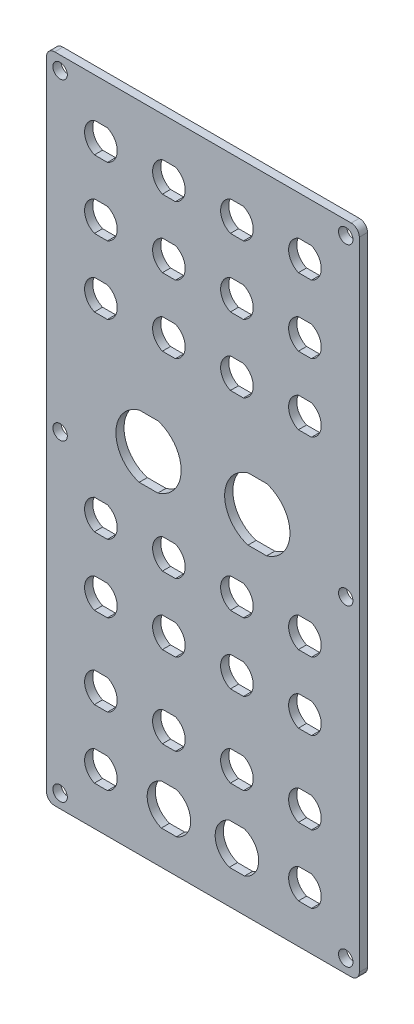
SolidWorks part; units mm, degrees
ref_plane "Front Plane" through (0, 0, 0) normal (0, 0, 1) x (1, 0, 0)
ref_plane "Top Plane" through (0, 0, 0) normal (0, 1, 0) x (1, 0, 0)
ref_plane "Right Plane" through (0, 0, 0) normal (1, 0, 0) x (0, 0, -1)
sketch "Sketch1" plane through (0, 0, 0) normal (0, 0, 1) x (1, 0, 0)
  line L1 (0, 0) -> (115, 0)
  line L2 (0, 0) -> (0, 240)
  line L3 (0, 240) -> (115, 240)
  line L4 (115, 0) -> (115, 240)
  dimension "D1" = 240
  dimension "D2" = 115
extrude "Boss-Extrude1" add sketch "Sketch1" along normal blind 3
sketch "Sketch2" plane through (0, 0, 3) normal (0, 0, 1) x (1, 0, 0)
  line L0 (20, 14.5) -> (20, 25.5) construction
  line L1 (22.3979, 25.5) -> (17.6021, 25.5)
  line L2 (22.3979, 14.5) -> (17.6021, 14.5)
  line L3 (0, 0) -> (115, 0) construction
  line L4 (0, 240) -> (0, 0) construction
  arc A0 (17.6021, 25.5) -> (17.6021, 14.5) centre (20, 20) ccw
  arc A1 (22.3979, 14.5) -> (22.3979, 25.5) centre (20, 20) ccw
  point P7 (20, 20)
  dimension "D2" = 12
  dimension "D1" = 11
  dimension "D3" = 20
  dimension "D4" = 20
extrude "Cut-Extrude1" cut sketch "Sketch2" against normal up to surface (3 mm away) up to face at (57.5, 120, 0)
pattern_linear "LPattern1" count 4 spacing 25 along (1, 0, 0) count 2 spacing 25 along (0, 1, 0) skipping (1, 0), (2, 0) of "Cut-Extrude1"
sketch "Sketch3" plane through (0, 0, 3) normal (0, 0, 1) x (1, 0, 0)
  line L0 (0, 120) -> (115, 120) construction
  line L1 (0, 240) -> (0, 0) construction
  line L2 (115, 0) -> (115, 240) construction
  line L3 (17.6021, 14.5) -> (22.3979, 14.5) construction
  line L4 (22.3979, 25.5) -> (17.6021, 25.5) construction
  line L5 (17.6021, 14.5) -> (22.3979, 14.5) construction
  line L6 (22.3979, 25.5) -> (17.6021, 25.5) construction
  line L7 (22.3979, 214.5) -> (17.6021, 214.5)
  line L8 (17.6021, 225.5) -> (22.3979, 225.5)
  arc A0 (17.6021, 25.5) -> (17.6021, 14.5) centre (20, 20) ccw construction
  arc A1 (22.3979, 14.5) -> (22.3979, 25.5) centre (20, 20) ccw construction
  arc A2 (17.6021, 25.5) -> (17.6021, 14.5) centre (20, 20) ccw construction
  arc A3 (22.3979, 14.5) -> (22.3979, 25.5) centre (20, 20) ccw construction
  arc A4 (22.3979, 225.5) -> (22.3979, 214.5) centre (20, 220) cw
  arc A5 (17.6021, 214.5) -> (17.6021, 225.5) centre (20, 220) cw
extrude "Cut-Extrude2" cut sketch "Sketch3" against normal up to surface (3 mm away) up to face at (95, 20, 0)
pattern_linear "LPattern2" count 4 spacing 25 along (1, 0, 0) count 3 spacing 25 along (0, -1, 0) of "Cut-Extrude2"
sketch "Sketch4" plane through (0, 0, 3) normal (0, 0, 1) x (1, 0, 0)
  line L0 (20, 25.5) -> (20, 14.5) construction
  line L1 (22.3979, 25.5) -> (17.6021, 25.5) construction
  line L2 (17.6021, 14.5) -> (22.3979, 14.5) construction
  line L3 (39, 45) -> (51, 45) construction
  line L4 (42.2161, 27.5) -> (47.7839, 27.5)
  line L5 (45, 12.5) -> (45, 27.5) construction
  line L6 (47.7839, 12.5) -> (42.2161, 12.5)
  arc A0 (42.2161, 27.5) -> (42.2161, 12.5) centre (45, 20) ccw
  arc A1 (42.6021, 50.5) -> (42.6021, 39.5) centre (45, 45) ccw construction
  arc A2 (47.3979, 39.5) -> (47.3979, 50.5) centre (45, 45) ccw construction
  arc A3 (47.7839, 12.5) -> (47.7839, 27.5) centre (45, 20) ccw
  point P16 (45, 45)
  point P17 (20, 20)
  point P24 (45, 20)
  dimension "D1" = 16
  dimension "D2" = 15
extrude "Cut-Extrude3" cut sketch "Sketch4" against normal up to surface (3 mm away) up to face at (45, 220, 0)
ref_plane "Plane2" through (57.5, 0, 0) normal (-1, 0, 0) x (0, 0, 1)
mirror "Mirror2" about plane through (57.5, 0, 0) normal (-1, 0, 0) of "Cut-Extrude3"
sketch "Sketch5" plane through (0, 0, 3) normal (0, 0, 1) x (1, 0, 0)
  line L0 (14, 45) -> (26, 45) construction
  line L1 (22.3979, 80.5) -> (17.6021, 80.5)
  line L2 (20, 69.5) -> (20, 80.5) construction
  line L3 (17.6021, 69.5) -> (22.3979, 69.5)
  arc A0 (17.6021, 80.5) -> (17.6021, 69.5) centre (20, 75) ccw
  arc A1 (17.6021, 50.5) -> (17.6021, 39.5) centre (20, 45) ccw construction
  arc A2 (22.3979, 39.5) -> (22.3979, 50.5) centre (20, 45) ccw construction
  arc A3 (22.3979, 69.5) -> (22.3979, 80.5) centre (20, 75) ccw
  point P10 (20, 45)
  point P18 (20, 75)
  dimension "D3" = 6
  dimension "D1" = 30
  dimension "D2" = 11
extrude "Cut-Extrude4" cut sketch "Sketch5" against normal up to surface (3 mm away) up to face at (45, 20, 0)
pattern_linear "LPattern3" count 4 spacing 25 along (1, 0, 0) count 2 spacing 25 along (0, 1, 0) of "Cut-Extrude4"
sketch "Sketch7" plane through (0, 0, 3) normal (0, 0, 1) x (1, 0, 0)
  line L0 (20, 100) -> (45, 100) construction
  line L1 (34.0722, 141.5) -> (40.9278, 141.5)
  line L2 (40.9278, 141.5) -> (40.9278, 118.5) construction
  line L3 (40.9278, 118.5) -> (34.0722, 118.5)
  line L4 (45, 100) -> (70, 100) construction
  arc A0 (34.0722, 141.5) -> (34.0722, 118.5) centre (37.5, 130) ccw
  arc A1 (40.9278, 118.5) -> (40.9278, 141.5) centre (37.5, 130) ccw
  point P1 (57.5, 100)
  dimension "D1" = 24
  dimension "D2" = 30
  dimension "D3" = 23
  dimension "D4" = 20
extrude "Cut-Extrude5" cut sketch "Sketch7" against normal up to surface (3 mm away) up to face at (45, 75, 0)
mirror "Mirror3" about plane through (57.5, 0, 0) normal (-1, 0, 0) of "Cut-Extrude5"
hole_wizard "M5 Clearance Hole1" positions "Sketch10" profile "Sketch11" hole size "M5" standard "ANSI Metric" end condition up to next
sketch "Sketch10" plane through (0, 0, 3) normal (0, 0, 1) x (1, 0, 0)
  line L12 (5, 235) -> (5, 5)
  line L13 (5, 5) -> (110, 5)
  line L14 (110, 5) -> (110, 235)
  line L15 (110, 235) -> (5, 235)
  line L16 (5, 235) -> (5, 5)
  line L17 (5, 5) -> (110, 5)
  line L18 (110, 5) -> (110, 235)
  line L19 (110, 235) -> (5, 235)
  point P25 (5, 235)
  point P26 (5, 5)
  point P27 (110, 5)
  point P28 (110, 235)
  point P31 (5, 120)
  point P37 (110, 120)
  dimension "D1" = 5
sketch "Sketch11" plane through (5, 235, 3) normal (1, 0, 0) x (0, -1, 0)
  line L0 (0, 0) -> (0, 3)
  line L1 (0, 3) -> (2.65, 3)
  line L2 (2.65, 3) -> (2.65, 0)
  line L5 (2.65, 0) -> (0, 0)
  line L11 (0, -6.35) -> (0, 107.95) construction
  dimension "Thru Hole Dia." = 5.3
  dimension "Thru Hole Depth" = 3
fillet "Fillet1" radius 3 4 edges at (0, 240, 1.5) (115, 240, 1.5) (115, 0, 1.5) (0, 0, 1.5)
